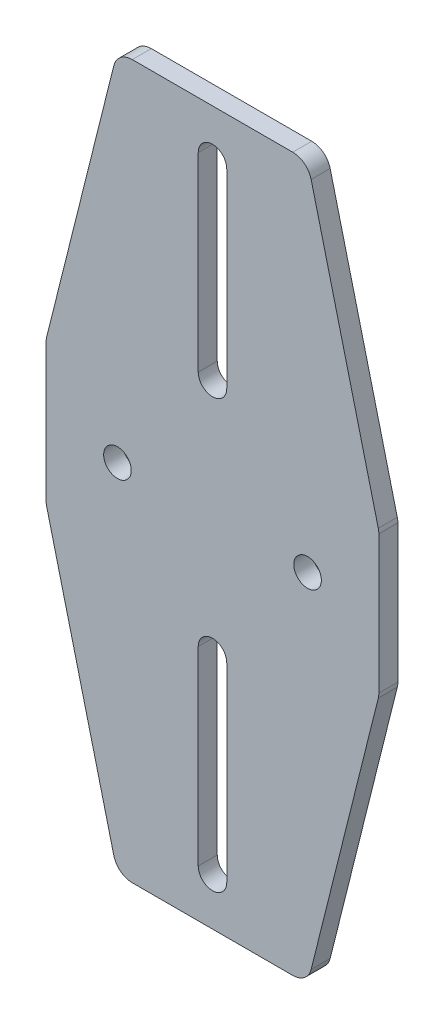
SolidWorks part; units mm, degrees
material "Thornel Mat VMA"
ref_plane "前视基准面" through (0, 0, 0) normal (0, 0, 1) x (1, 0, 0)
ref_plane "上视基准面" through (0, 0, 0) normal (0, 1, 0) x (1, 0, 0)
ref_plane "右视基准面" through (0, 0, 0) normal (1, 0, 0) x (0, 0, -1)
other "Configuration Table"
sketch "草图1" plane through (0, 0, 0) normal (0, 0, 1) x (1, 0, 0)
  line L0 (0, 0) -> (7.5, 30)
  line L2 (0, 0) -> (0, -15)
  line L3 (0, -15) -> (35, -15) construction
  line L4 (35, 0) -> (35, -15)
  line L5 (7.5, 30) -> (27.5, 30)
  line L6 (27.5, 30) -> (35, 0)
  line L7 (0, -7.5) -> (35, -7.5) construction
  line L8 (27.5, -45) -> (35, -15)
  line L9 (7.5, -45) -> (27.5, -45)
  line L10 (0, -15) -> (7.5, -45)
  dimension "D1" = 15
  dimension "D2" = 35
  dimension "D3" = 20
  dimension "D4" = 45
extrude "凸台-拉伸1" add sketch "草图1" along normal blind 2
sketch "草图2" plane through (0, 0, 2) normal (0, 0, 1) x (1, 0, 0)
  line L0 (0, -7.5) -> (35, -7.5) construction
  line L1 (0, 0) -> (0, -15) construction
  line L2 (35, -15) -> (35, 0) construction
  line L3 (17.5, 30) -> (17.5, -7.5) construction
  line L4 (27.5, 30) -> (7.5, 30) construction
  line L6 (17.5, 25) -> (17.5, 5) construction
  line L7 (19, 25) -> (19, 5)
  line L8 (16, 25) -> (16, 5)
  line L9 (17.5, -40) -> (17.5, -20) construction
  line L10 (19, -40) -> (19, -20)
  line L11 (16, -40) -> (16, -20)
  circle A0 centre (7.5, -7.5) radius 1.45
  arc A1 (19, 25) -> (16, 25) centre (17.5, 25) ccw
  arc A2 (16, 5) -> (19, 5) centre (17.5, 5) ccw
  circle A3 centre (27.5, -7.5) radius 1.45
  arc A4 (19, -40) -> (16, -40) centre (17.5, -40) cw
  arc A5 (16, -20) -> (19, -20) centre (17.5, -20) cw
  point P16 (17.5, 15)
  point P26 (17.5, -30)
  dimension "D1" = 3
  dimension "D2" = 2.9
  dimension "D3" = 10
  dimension "D4" = 5
  dimension "D5" = 5
extrude "切除-拉伸1" cut sketch "草图2" against normal through all
fillet "圆角1" radius 2 8 edges at (27.5, 30, 1) (35, 0, 1) (0, 0, 1) (7.5, 30, 1) (35, -15, 1) (27.5, -45, 1) (7.5, -45, 1) (0, -15, 1)
